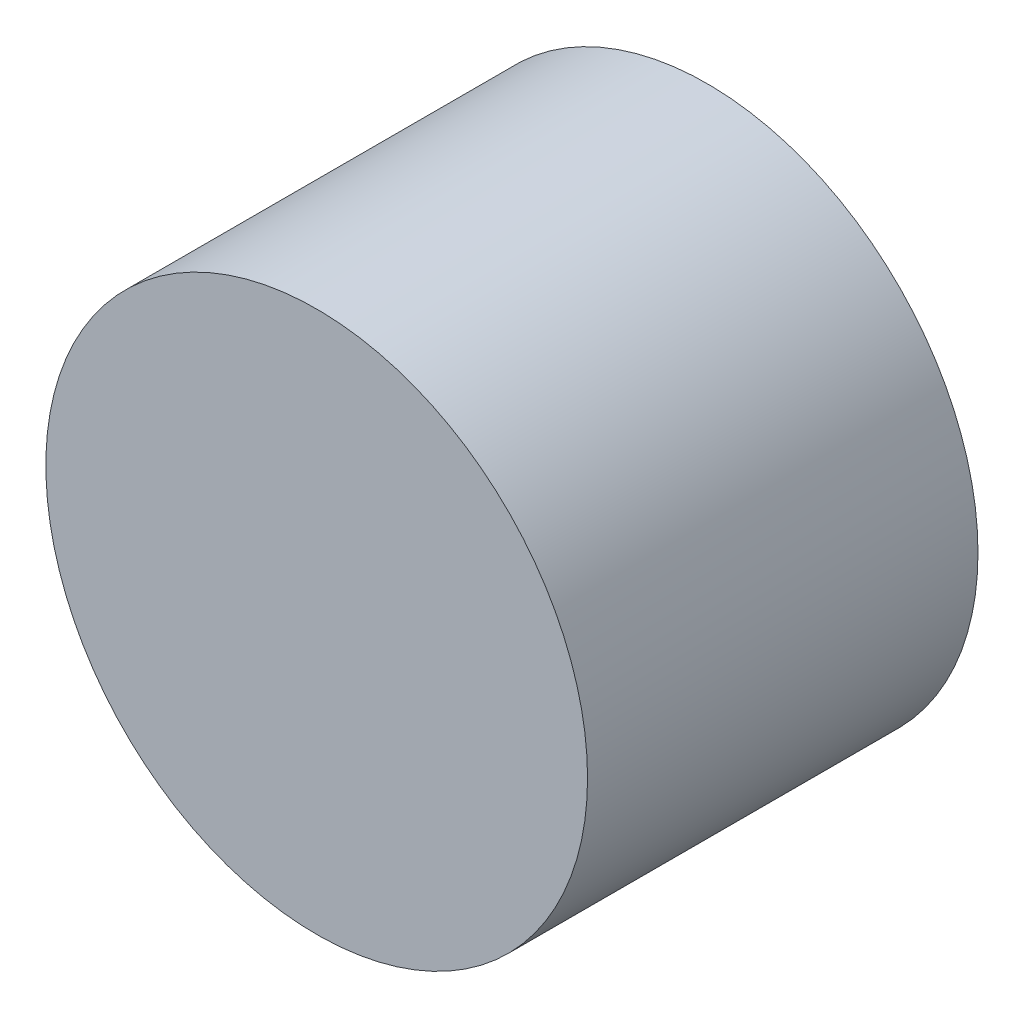
SolidWorks part; units mm, degrees
material "Titanium"
ref_plane "Front Plane" through (0, 0, 0) normal (0, 0, 1) x (1, 0, 0)
ref_plane "Top Plane" through (0, 0, 0) normal (0, 1, 0) x (1, 0, 0)
ref_plane "Right Plane" through (0, 0, 0) normal (1, 0, 0) x (0, 0, -1)
sketch "Sketch1" plane through (0, 0, 0) normal (0, 0, 1) x (1, 0, 0)
  circle A0 centre (0, 0) radius 1.3875
  dimension "D1" = 2.775
extrude "Boss-Extrude1" add sketch "Sketch1" along normal blind 2
